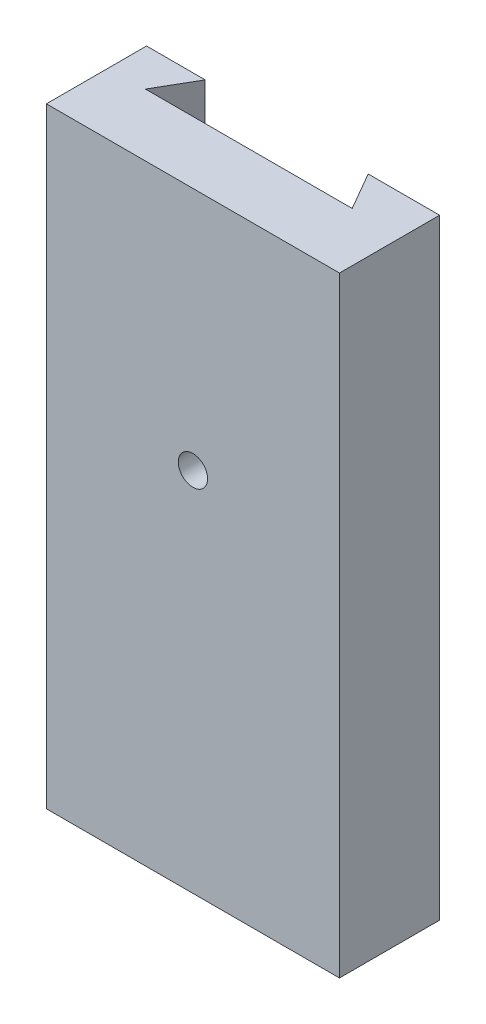
SolidWorks part; units mm, degrees
ref_plane "Front Plane" through (0, 0, 0) normal (0, 0, 1) x (1, 0, 0)
ref_plane "Top Plane" through (0, 0, 0) normal (0, 1, 0) x (1, 0, 0)
ref_plane "Right Plane" through (0, 0, 0) normal (1, 0, 0) x (0, 0, -1)
sketch "Sketch1" plane through (0, 0, 0) normal (0, 1, 0) x (1, 0, 0)
  line L1 (-60, -20.5) -> (60, -20.5)
  line L2 (-60, -20.5) -> (-60, 20.5)
  line L3 (-60, 20.5) -> (60, 20.5)
  line L4 (60, -20.5) -> (60, 20.5)
  line L5 (-60, -20.5) -> (60, 20.5) construction
  line L6 (-60, 20.5) -> (60, -20.5) construction
  point P0 (0, 0)
  dimension "D1" = 120
  dimension "D2" = 41
extrude "Boss-Extrude1" add sketch "Sketch1" along normal blind 250
sketch "Sketch2" plane through (0, 250, 0) normal (0, 1, 0) x (1, 0, 0)
  line L0 (-36, 20.5) -> (-44.9489, 5)
  line L1 (60, 20.5) -> (-60, 20.5) construction
  line L2 (30.76, 20.5) -> (39.7089, 5)
  line L3 (-44.9489, 5) -> (39.7089, 5)
  line L4 (-36, 20.5) -> (30.76, 20.5)
  dimension "D1" = 29.24
  dimension "D2" = 60
  dimension "D3" = 15.5
  dimension "D4" = 24
  dimension "D5" = 60
  dimension "D6" = 15.5
extrude "Cut-Extrude1" cut sketch "Sketch2" against normal blind 250
sketch "Sketch3" plane through (0, 0, 20.5) normal (0, 0, 1) x (1, 0, 0)
  line L0 (-60, 250) -> (60, 250) construction
  circle A0 centre (0, 150) radius 6
  dimension "D2" = 12
  dimension "D1" = 100
extrude "Cut-Extrude2" cut sketch "Sketch3" against normal blind 250
